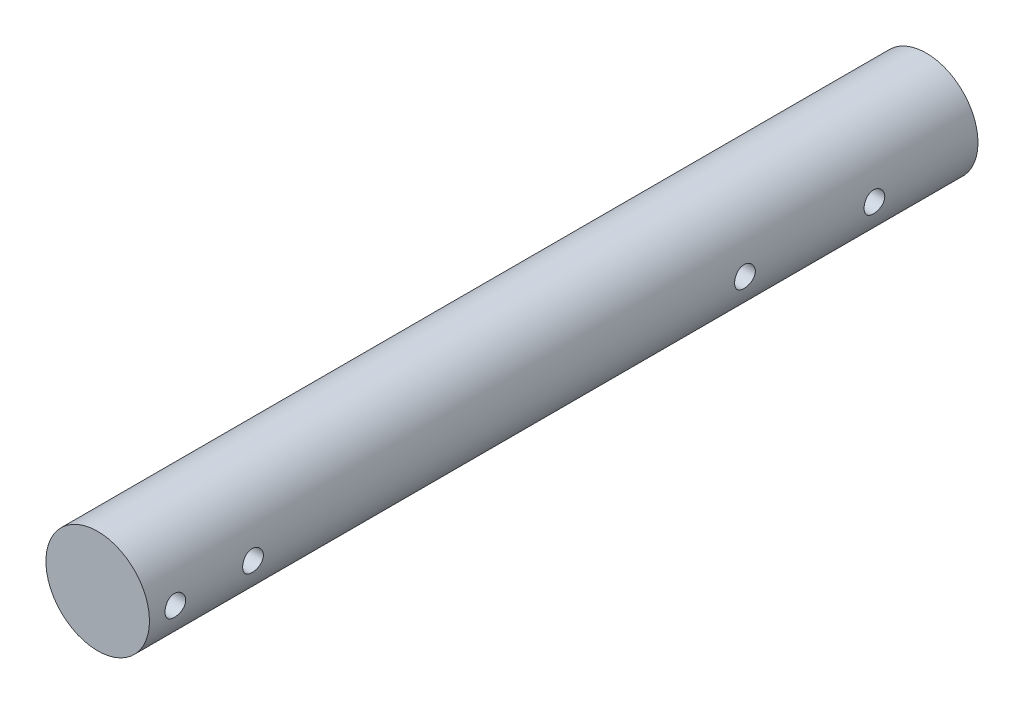
SolidWorks part; units mm, degrees
material "PA Type 6"
ref_plane "Front Plane" through (0, 0, 0) normal (0, 0, 1) x (1, 0, 0)
ref_plane "Top Plane" through (0, 0, 0) normal (0, 1, 0) x (1, 0, 0)
ref_plane "Right Plane" through (0, 0, 0) normal (1, 0, 0) x (0, 0, -1)
sketch "Sketch1" plane through (0, 0, 0) normal (0, 0, 1) x (1, 0, 0)
  circle A0 centre (0, 0) radius 20
  dimension "D1" = 40
extrude "Boss-Extrude1" add sketch "Sketch1" along normal blind 320
sketch "Sketch2" plane through (0, 0, 0) normal (1, 0, 0) x (0, 0, -1)
  line L0 (0, -20) -> (0, 20) construction
  line L1 (0, 20) -> (-320, 20) construction
  line L2 (0, 20) -> (-320, 20) construction
  line L3 (-320, 20) -> (-320, -20) construction
  circle A0 centre (-40, 0) radius 4
  circle A1 centre (-90, 0) radius 4
  circle A2 centre (-310, 0) radius 4
  circle A3 centre (-280, 0) radius 4
  dimension "D1" = 8
  dimension "D2" = 40
  dimension "D3" = 20
  dimension "D4" = 8
  dimension "D5" = 50
  dimension "D6" = 20
  dimension "D7" = 8
  dimension "D8" = 20
  dimension "D9" = 10
  dimension "D10" = 8
  dimension "D11" = 20
  dimension "D12" = 40
extrude "Cut-Extrude1" cut sketch "Sketch2" against normal through all both and the other way through all
